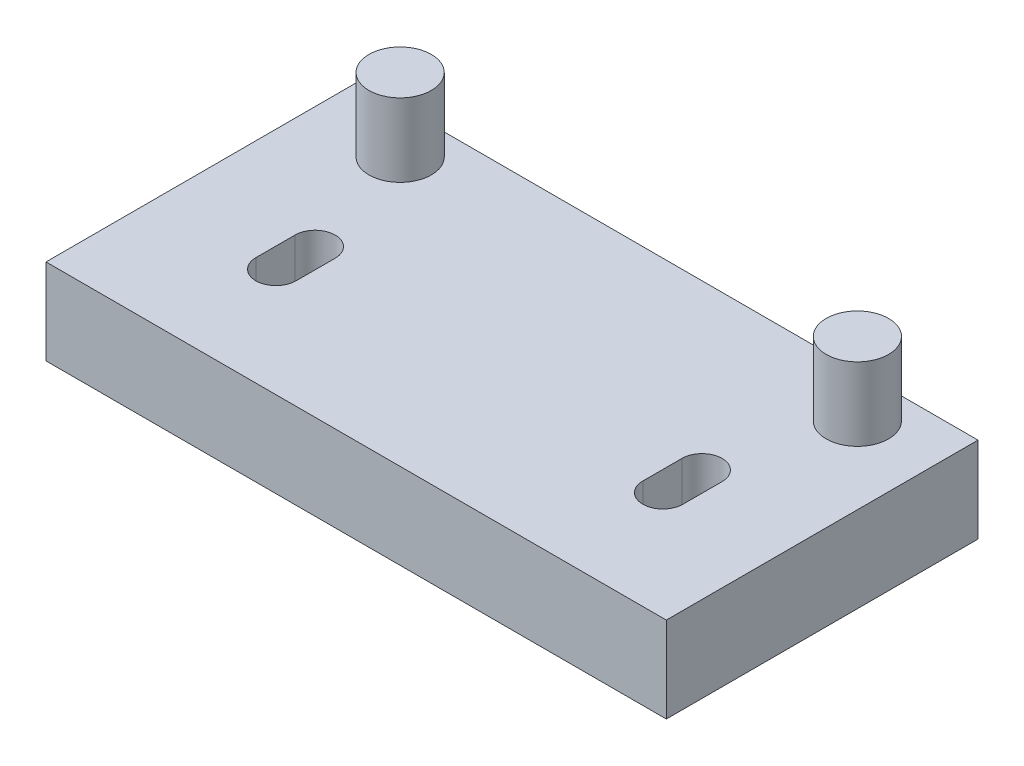
SolidWorks part; units mm, degrees
ref_plane "Front Plane" through (0, 0, 0) normal (0, 0, 1) x (1, 0, 0)
ref_plane "Top Plane" through (0, 0, 0) normal (0, 1, 0) x (1, 0, 0)
ref_plane "Right Plane" through (0, 0, 0) normal (1, 0, 0) x (0, 0, -1)
sketch "Sketch1" plane through (0, 0, 0) normal (0, 1, 0) x (1, 0, 0)
  line L1 (-152.9271, 75.7175) -> (148.4511, 75.7175)
  line L2 (-152.9271, 75.7175) -> (-152.9271, -75.7175)
  line L3 (-152.9271, -75.7175) -> (148.4511, -75.7175)
  line L4 (148.4511, 75.7175) -> (148.4511, -75.7175)
  point P0 (-2.238, 0)
extrude "Boss-Extrude1" add sketch "Sketch1" along normal blind 41.656
sketch "Sketch2" plane through (0, 41.656, 0) normal (0, 1, 0) x (1, 0, 0)
  line L0 (-103.7531, -3.9044) -> (-103.7531, -22.9385)
  line L1 (-84.2309, -22.9385) -> (-84.2309, -3.9044)
  arc A0 (-103.7531, -22.9385) -> (-84.2309, -22.9385) centre (-93.992, -22.9385) ccw
  arc A1 (-84.2309, -3.9044) -> (-103.7531, -3.9044) centre (-93.992, -3.9044) ccw
extrude "Cut-Extrude1" cut sketch "Sketch2" against normal blind 214.376
sketch "Sketch3" plane through (0, 41.656, 0) normal (0, 1, 0) x (1, 0, 0)
  circle A0 centre (-111.0739, 54.4876) radius 15.1611
extrude "Boss-Extrude2" add sketch "Sketch3" along normal blind 35.56
mirror "Mirror1" about plane through (0, 0, 0) normal (1, 0, 0) of "Cut-Extrude1", "Boss-Extrude2"
